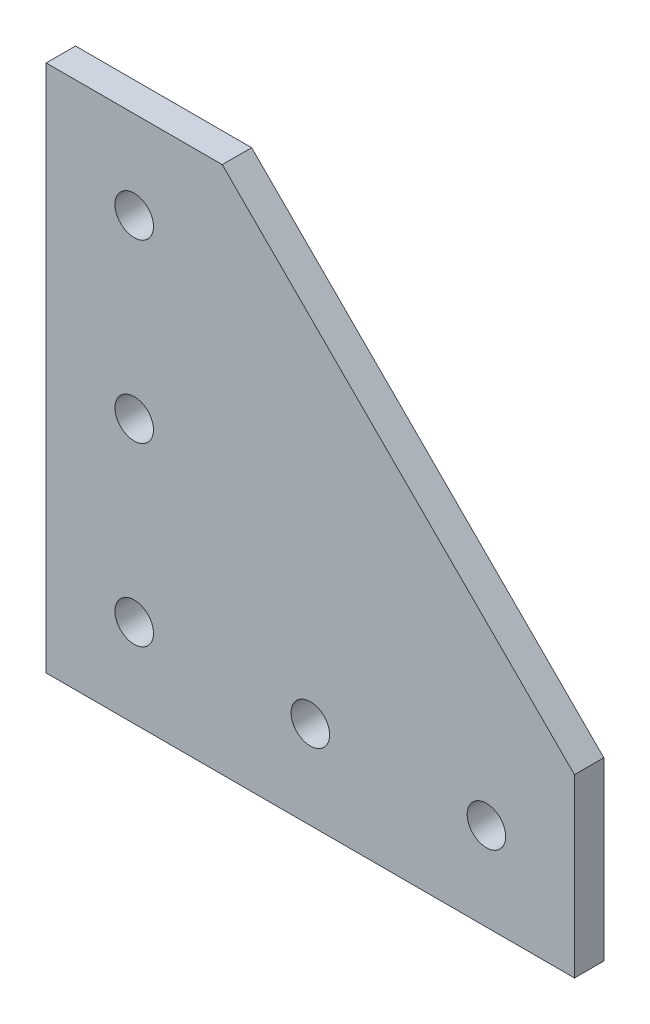
SolidWorks part; units mm, degrees
ref_plane "Front"
ref_plane "Top" through (0, 0, 0) normal (0, 1, 0) x (1, 0, 0)
ref_plane "Right" through (0, 0, 0) normal (1, 0, 0) x (0, 0, -1)
sketch "Sketch1" plane through (0, 0, 0) normal (0, 0, 1) x (1, 0, 0)
  line L0 (0, 0) -> (0, 114.3)
  line L1 (0, 114.3) -> (38.1, 114.3)
  line L2 (38.1, 114.3) -> (114.3, 38.1)
  line L3 (114.3, 38.1) -> (114.3, 0)
  line L4 (114.3, 0) -> (0, 0)
  dimension "HeightY" = 114.3
  dimension "WidthX" = 114.3
  dimension "CornerX" = 38.1
  dimension "CornerY" = 38.1
extrude "Base Extrude" add sketch "Sketch1" along normal blind 6.35
sketch "Sketch2" plane through (0, 0, 6.35) normal (0, 0, 1) x (1, 0, 0)
  line L0 (0, 114.3) -> (0, 0) construction
  line L1 (0, 0) -> (114.3, 0) construction
  circle A0 centre (19.05, 19.05) radius 4.1656
  dimension "Hole1Diam" = 8.3312
  dimension "Hole1X" = 19.05
  dimension "Hole1Y" = 19.05
extrude "Hole1" cut sketch "Sketch2" against normal through all
pattern_linear "Hole1 Pattern"
sketch "Sketch3" plane through (0, 0, 6.35) normal (0, 0, 1) x (1, 0, 0)
  line L0 (0, 0) -> (114.3, 0) construction
  line L1 (0, 114.3) -> (0, 0) construction
  circle A0 centre (19.05, 57.15) radius 4.1656
  dimension "Hole2Diam" = 8.3312
  dimension "Hole2Y" = 57.15
  dimension "Hole2X" = 19.05
extrude "Hole2" cut sketch "Sketch3" against normal through all
pattern_linear "Hole2 Pattern"
ref_plane "Mate 1" through (0, 0, 6.35) normal (0, 0, 1) x (1, 0, 0)
ref_plane "Mate 2" through (0, 0, 0) normal (0, -1, 0) x (1, 0, 0)
ref_plane "Mate 3" through (0, 0, 0) normal (-1, 0, 0) x (0, 0, 1)
ref_plane "Mate 4" through (0, 19.05, 0) normal (0, -1, 0) x (1, 0, 0)
ref_plane "Mate 5" through (0, 57.15, 0) normal (0, -1, 0) x (1, 0, 0)
ref_plane "Mate 6" through (0, 95.25, 0) normal (0, -1, 0) x (1, 0, 0)
ref_plane "Mate 7"
ref_plane "Mate 8" through (19.05, 0, 0) normal (-1, 0, 0) x (0, 0, 1)
ref_plane "Mate 9" through (57.15, 0, 0) normal (-1, 0, 0) x (0, 0, 1)
ref_plane "Mate 10" through (95.25, 0, 0) normal (-1, 0, 0) x (0, 0, 1)
ref_plane "Mate 11"
ref_plane "Mate 12"
ref_plane "Mate 13"
ref_plane "Mate 14"
ref_plane "Mate 15"
ref_plane "Mate 16"
ref_plane "Mate 17"
ref_plane "Mate 18"
ref_plane "Mate 19"
